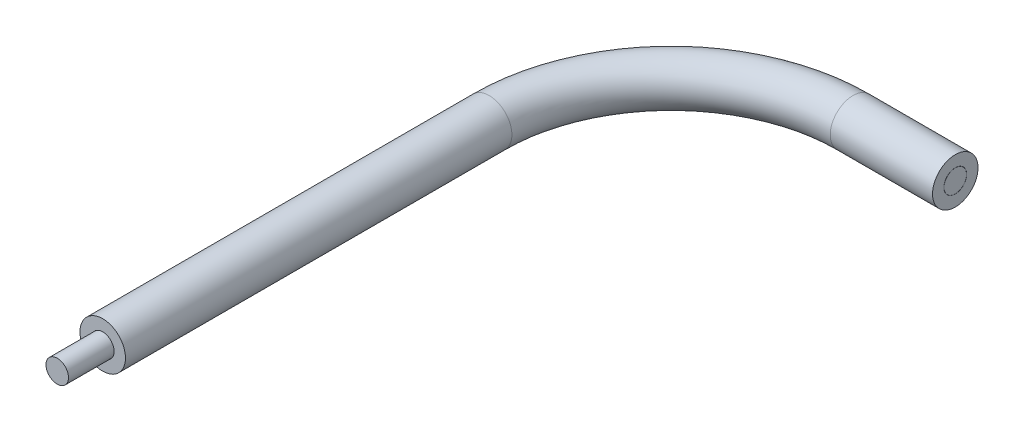
SolidWorks part; units mm, degrees
ref_plane "前视基准面" through (0, 0, 0) normal (0, 0, 1) x (1, 0, 0)
ref_plane "上视基准面" through (0, 0, 0) normal (0, 1, 0) x (1, 0, 0)
ref_plane "右视基准面" through (0, 0, 0) normal (1, 0, 0) x (0, 0, -1)
sketch "草图1" plane through (0, 0, 0) normal (0, 1, 0) x (1, 0, 0)
  line L0 (0, 0) -> (0, 25) construction
  line L1 (0, 25) -> (10.0097, 25) construction
  line L2 (0, 17) -> (0, 0)
  line L3 (8, 25) -> (12.5, 25)
  line L4 (8, 25) -> (8, 17) construction
  line L5 (8, 17) -> (0, 17) construction
  arc A0 (8, 25) -> (0, 17) centre (8, 17) ccw
  dimension "D6" = 8
  dimension "D2" = 4.5
  dimension "D3" = 25
sketch "草图2" plane through (0, 0, 0) normal (0, 0, 1) x (1, 0, 0)
  circle A0 centre (0, 0) radius 1
  circle A1 centre (0, 0) radius 0.5
  dimension "D1" = 2
  dimension "D2" = 1
sweep "扫描1" add profiles "草图2" path "草图1"
sketch "草图3" plane through (0, 0, 0) normal (0, 1, 0) x (1, 0, 0)
  line L0 (0, 17) -> (0, 0) construction
  line L1 (8, 25) -> (12.5, 25) construction
  line L2 (0, 17) -> (0, 0)
  line L3 (8, 25) -> (12.5, 25)
  line L4 (0, 0) -> (0, -2)
  arc A0 (8, 25) -> (0, 17) centre (8, 17) ccw construction
  arc A1 (8, 25) -> (0, 17) centre (8, 17) ccw
  dimension "D1" = 2
sketch "草图4" plane through (0, 0, 0) normal (0, 0, 1) x (1, 0, 0)
  circle A3 centre (0, 0) radius 0.495
  dimension "D1" = 0.99
sweep "扫描2" add profiles "草图4" path "草图3"
